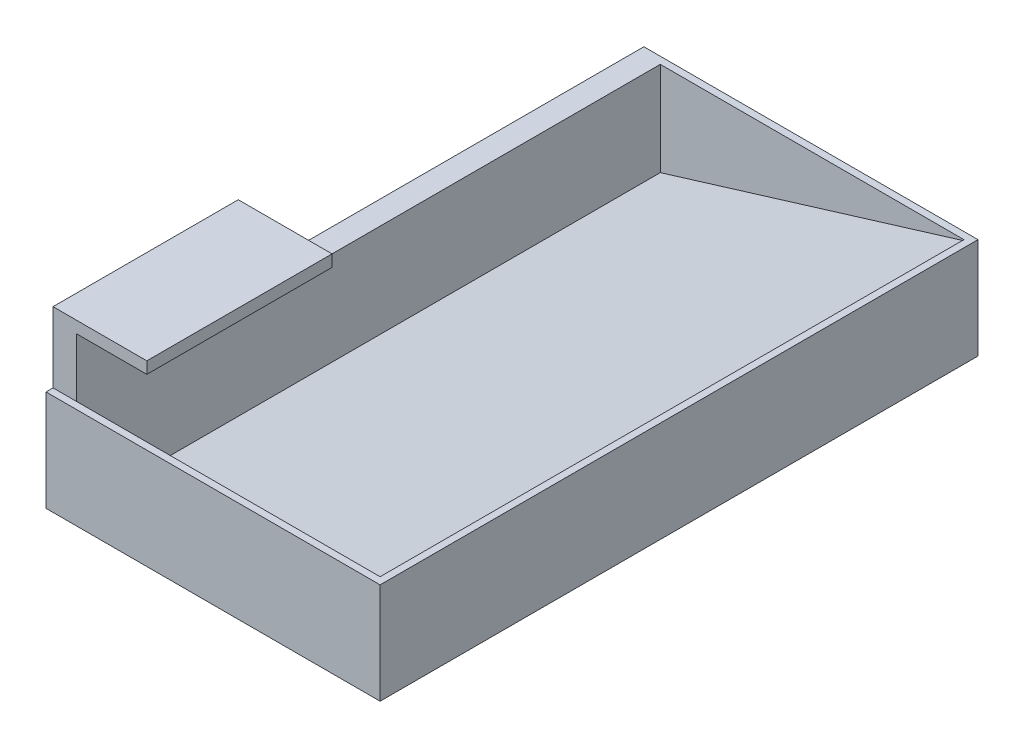
SolidWorks part; units mm, degrees
ref_plane "Front Plane" through (0, 0, 0) normal (0, 0, 1) x (1, 0, 0)
ref_plane "Top Plane" through (0, 0, 0) normal (0, 1, 0) x (1, 0, 0)
ref_plane "Right Plane" through (0, 0, 0) normal (1, 0, 0) x (0, 0, -1)
sketch "Sketch1" plane through (0, 0, 0) normal (0, 1, 0) x (1, 0, 0)
  line L1 (0, 0) -> (142.5, 0)
  line L2 (0, 0) -> (0, 255)
  line L3 (0, 255) -> (142.5, 255)
  line L4 (142.5, 0) -> (142.5, 255)
  dimension "D1" = 142.5
  dimension "D2" = 255
extrude "Boss-Extrude1" add sketch "Sketch1" along normal blind 43
sketch "Sketch2" plane through (0, 43, 0) normal (0, 1, 0) x (1, 0, 0)
  line L0 (142.5, 255) -> (0, 255) construction
  line L1 (10, 3) -> (139.5, 3)
  line L2 (10, 3) -> (10, 252)
  line L3 (10, 252) -> (139.5, 252)
  line L4 (139.5, 3) -> (139.5, 252)
  line L5 (0, 255) -> (0, 0) construction
  line L6 (0, 0) -> (142.5, 0) construction
  line L7 (142.5, 0) -> (142.5, 255) construction
  dimension "D1" = 3
  dimension "D2" = 10
  dimension "D3" = 3
  dimension "D4" = 3
extrude "Cut-Extrude1" cut sketch "Sketch2" against normal blind 40
ref_plane "Plane1" through (0, 0, -3) normal (0, 0, 1) x (1, 0, 0)
sketch "Sketch5" plane through (0, 0, -3) normal (0, 0, 1) x (1, 0, 0)
  line L0 (10, 43) -> (10, 68)
  line L1 (10, 68) -> (40, 68)
  line L2 (40, 68) -> (40, 73)
  line L3 (40, 73) -> (0, 73)
  line L4 (0, 73) -> (0, 43)
  line L5 (0, 43) -> (10, 43)
  dimension "D1" = 30
  dimension "D2" = 25
  dimension "D3" = 40
extrude "Boss-Extrude2" add sketch "Sketch5" against normal blind 79
sketch "Sketch6" plane through (0, 0, -3) normal (0, 0, 1) x (1, 0, 0)
  line L0 (10, 3) -> (139.5, 42.5921)
  line L1 (139.5, 3) -> (139.5, 43) construction
  line L2 (139.5, 42.5921) -> (139.5, 3)
  line L3 (10, 3) -> (139.5, 3) construction
  line L4 (139.5, 3) -> (10, 3)
  dimension "D1" = 17
extrude "Boss-Extrude3" add sketch "Sketch6" against normal blind 250
